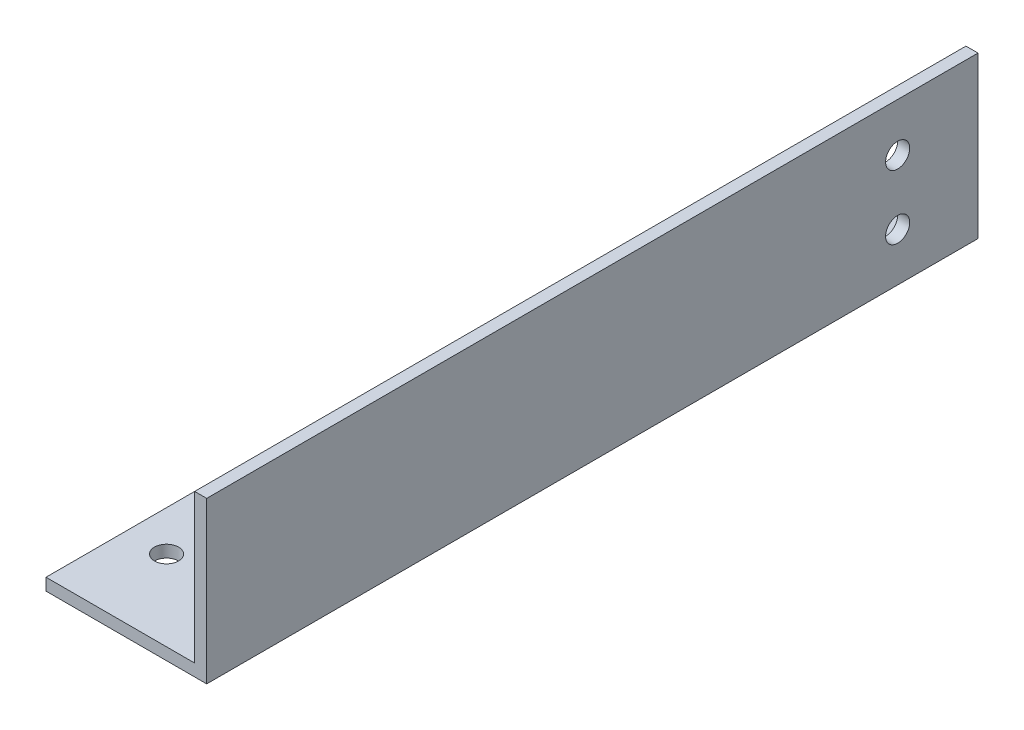
SolidWorks part; units mm, degrees
ref_plane "Plan de face" through (0, 0, 0) normal (0, 0, 1) x (1, 0, 0)
ref_plane "Plan de dessus" through (0, 0, 0) normal (0, 1, 0) x (1, 0, 0)
ref_plane "Plan de droite" through (0, 0, 0) normal (1, 0, 0) x (0, 0, -1)
sketch "Esquisse1" plane through (0, 0, 0) normal (0, 0, 1) x (1, 0, 0)
  line L0 (-3.719, 18.5) -> (-3.719, -1.5)
  line L1 (-3.719, -1.5) -> (-23.719, -1.5)
  line L2 (-23.719, -1.5) -> (-23.719, 0)
  line L3 (-23.719, 0) -> (-5.219, 0)
  line L4 (-5.219, 0) -> (-5.219, 18.5)
  line L5 (-5.219, 18.5) -> (-3.719, 18.5)
  dimension "D1" = 1.5
  dimension "D2" = 1.5
  dimension "D3" = 20
  dimension "D4" = 20
extrude "Extrusion1" add sketch "Esquisse1" along normal blind 96
sketch "Esquisse2" plane through (0, -1.5, 0) normal (0, -1, 0) x (1, 0, 0)
  line L0 (-23.719, 96) -> (-3.719, 96) construction
  line L1 (-23.719, 96) -> (-23.719, 0) construction
  line L2 (-3.719, 96) -> (-3.719, 0) construction
  circle A0 centre (-8.719, 86) radius 1.5
  circle A1 centre (-18.719, 86) radius 1.5
  dimension "D1" = 10
  dimension "D2" = 10
  dimension "D3" = 5
  dimension "D4" = 5
extrude "Extrusion2" cut sketch "Esquisse2" against normal blind 70
sketch "Esquisse3" plane through (-3.719, 0, 0) normal (1, 0, 0) x (0, 0, -1)
  line L0 (0, -1.5) -> (0, 18.5) construction
  line L1 (-96, 18.5) -> (0, 18.5) construction
  circle A0 centre (-10, 12.5) radius 1.5
  circle A1 centre (-10, 4.5) radius 1.5
  dimension "D1" = 10
  dimension "D2" = 10
  dimension "D3" = 8
  dimension "D4" = 6
extrude "Extrusion3" cut sketch "Esquisse3" against normal blind 10
